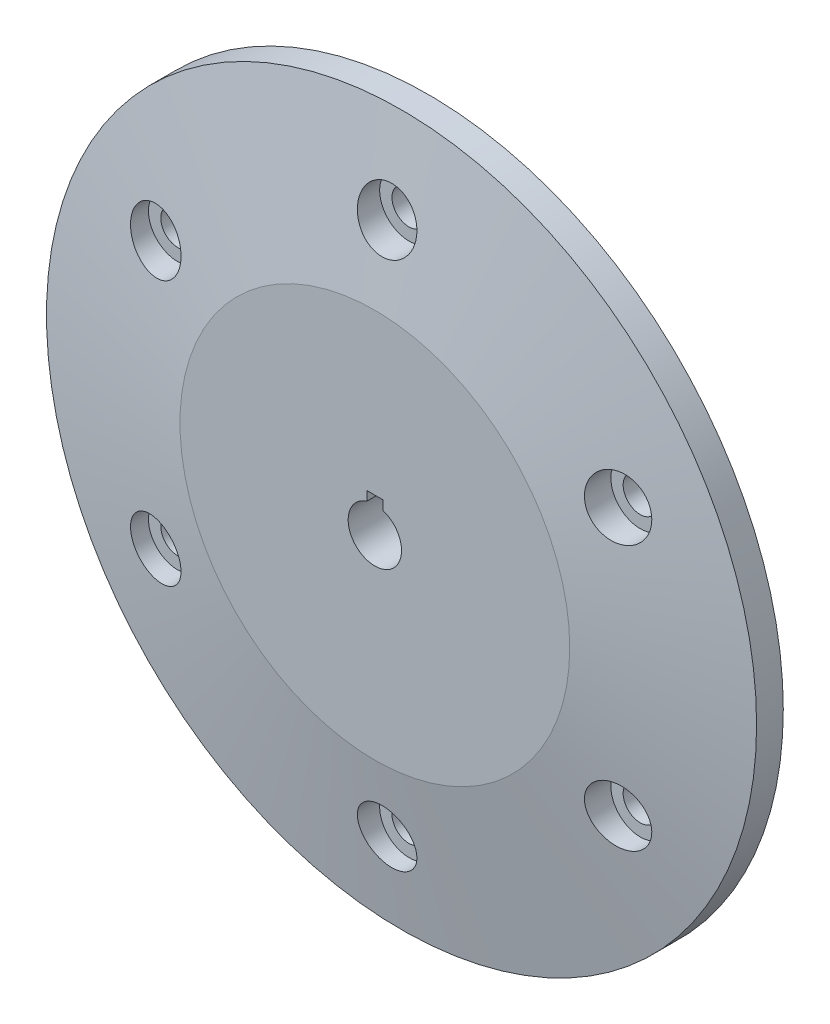
SolidWorks part; units mm, degrees
ref_plane "Front Plane" through (0, 0, 0) normal (0, 0, 1) x (1, 0, 0)
ref_plane "Top Plane" through (0, 0, 0) normal (0, 1, 0) x (1, 0, 0)
ref_plane "Right Plane" through (0, 0, 0) normal (1, 0, 0) x (0, 0, -1)
sketch "Sketch1" plane through (0, 0, 0) normal (0, 1, 0) x (1, 0, 0)
  line L0 (0, 0) -> (0, -30)
  line L1 (0, 0) -> (15, 0)
  line L2 (15, 0) -> (15, -25)
  line L3 (15, -25) -> (30, -25)
  line L4 (42.8, -24) -> (42.8, -17)
  line L5 (42.8, -17) -> (44.8, -17)
  line L6 (44.8, -17) -> (44.8, -20)
  line L7 (44.8, -20) -> (66.5, -20)
  line L8 (66.5, -20) -> (66.5, -30)
  line L9 (66.5, -30) -> (0, -30)
  line L10 (0, -30) -> (0, 0) construction
  line L11 (42.8, -24) -> (30, -24)
  line L12 (30, -24) -> (30, -25)
  point P3 (44.8, -18.5)
  dimension "D1" = 89.6
  dimension "D2" = 30
  dimension "D3" = 2
  dimension "D4" = 133
  dimension "D5" = 3
  dimension "D6" = 8
  dimension "D7" = 25
  dimension "D8" = 10
  dimension "D9" = 30
  dimension "D10" = 6
revolve "Revolve1" add sketch "Sketch1" angle 360 about L10
sketch "Sketch2" plane through (0, 0, 0) normal (0, 0, -1) x (-1, 0, 0)
  line L1 (-1.5, 3.5) -> (1.5, 3.5)
  line L2 (-1.5, 3.5) -> (-1.5, 6.5)
  line L3 (-1.5, 6.5) -> (1.5, 6.5)
  line L4 (1.5, 3.5) -> (1.5, 6.5)
  circle A0 centre (0, 0) radius 5
  point P7 (0, 3.5)
  dimension "D1" = 10
  dimension "D2" = 3
  dimension "D3" = 3
  dimension "D4" = 3.5
extrude "Cut-Extrude1" cut sketch "Sketch2" against normal through all contours A0 L4 L3 L2 | L4 A0 L2 L1 | L2 A0 L4 L1
chamfer "Chamfer2" distance 5 distance2 30 1 edges at (66.5, 0, 30)
hole_wizard "CBORE for M6 Hex Socket Head Cap Screw1" positions "Sketch3" profile "Sketch4" counterbore size "M6" standard "ISO" end condition through all
sketch "Sketch3" plane through (0, 0, 30) normal (0, 0, 1) x (1, 0, 0)
  point P0 (0, 50)
  dimension "D1" = 50
sketch "Sketch4" plane through (0, 50, 30) normal (1, 0, 0) x (0, -1, 0)
  line L0 (0, 0) -> (0, 30)
  line L1 (0, 30) -> (3.2, 30)
  line L3 (3.2, 30) -> (3.2, 6.4)
  line L4 (3.2, 6.4) -> (5.5, 6.4)
  line L5 (5.5, 6.4) -> (5.5, 0)
  line L7 (5.5, 0) -> (0, 0)
  line L11 (0, -6.35) -> (0, 107.95) construction
  dimension "Thru Hole Dia." = 6.4
  dimension "Thru Hole Depth" = 30
  dimension "C'Bore Dia." = 11
  dimension "C'Bore Depth" = 6.4
pattern_circular "CirPattern1" count 6 over 360 about axis through (0, 0, 0) along (0, 0, 1) of "CBORE for M6 Hex Socket Head Cap Screw1"
move or copy body "Body-Move/Copy1" [suppressed] bodies to move or copy 104
